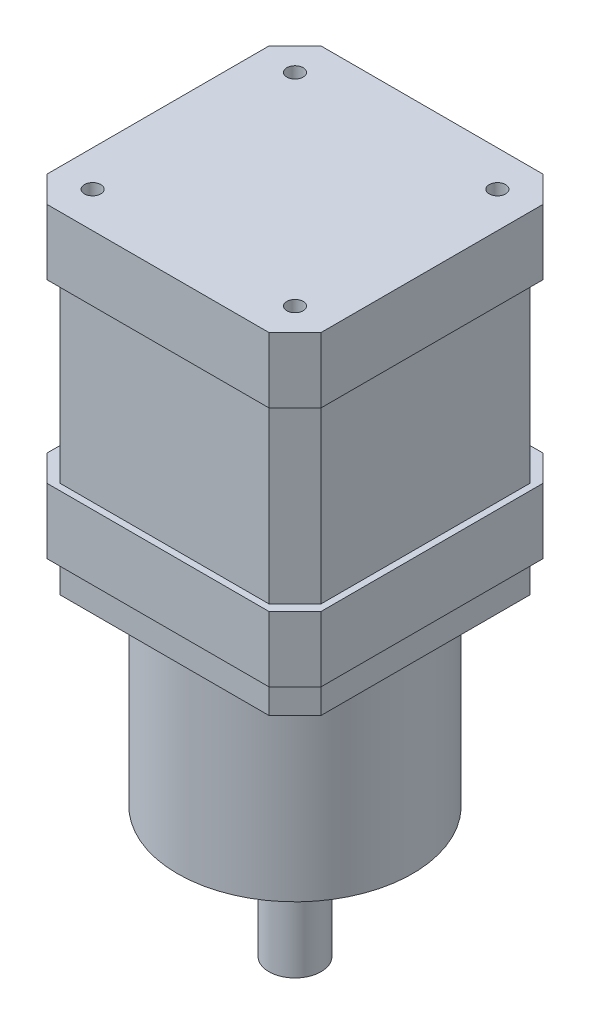
SolidWorks part; units mm, degrees
ref_plane "Front Plane" through (0, 0, 0) normal (0, 0, 1) x (1, 0, 0)
ref_plane "Top Plane" through (0, 0, 0) normal (0, 1, 0) x (1, 0, 0)
ref_plane "Right Plane" through (0, 0, 0) normal (1, 0, 0) x (0, 0, -1)
sketch "Sketch1" plane through (0, 0, 0) normal (0, 1, 0) x (1, 0, 0)
  line L1 (21, -21) -> (-21, -21)
  line L2 (21, -21) -> (21, 21)
  line L3 (21, 21) -> (-21, 21)
  line L4 (-21, -21) -> (-21, 21)
  line L5 (21, -21) -> (-21, 21) construction
  line L6 (21, 21) -> (-21, -21) construction
  point P0 (0, 0)
  dimension "D1" = 42
extrude "Boss-Extrude1" add sketch "Sketch1" along normal mid plane 47
sketch "Sketch2" plane through (0, 23.5, 0) normal (0, 1, 0) x (1, 0, 0)
  line L0 (-20, 20) -> (-20, -20)
  line L1 (-20, -20) -> (20, -20)
  line L2 (20, -20) -> (20, 20)
  line L3 (20, 20) -> (-20, 20)
  line L4 (-21, 21) -> (-21, -21)
  line L5 (-21, -21) -> (21, -21)
  line L6 (21, -21) -> (21, 21)
  line L7 (21, 21) -> (-21, 21)
  line L8 (-21, 21) -> (-21, -21)
  line L9 (-21, -21) -> (21, -21)
  line L10 (21, -21) -> (21, 21)
  line L11 (21, 21) -> (-21, 21)
  dimension "D1" = 0
  dimension "D2" = 1
extrude "Cut-Extrude1" cut sketch "Sketch2" against normal blind 27 from offset 10 offset against normal yes
chamfer "Chamfer1" distance 4 angle 45 1 edges at (-20, 0, 20)
sketch "Sketch4" plane through (0, 23.5, 0) normal (0, 1, 0) x (1, 0, 0)
  line L1 (-15.5, -15.5) -> (15.5, -15.5) construction
  line L2 (-15.5, -15.5) -> (-15.5, 15.5) construction
  line L3 (-15.5, 15.5) -> (15.5, 15.5) construction
  line L4 (15.5, -15.5) -> (15.5, 15.5) construction
  line L5 (-15.5, -15.5) -> (15.5, 15.5) construction
  line L6 (-15.5, 15.5) -> (15.5, -15.5) construction
  circle A0 centre (15.5, 15.5) radius 1.25
  circle A1 centre (15.5, -15.5) radius 1.25
  circle A2 centre (-15.5, -15.5) radius 1.25
  circle A3 centre (-15.5, 15.5) radius 1.25
  point P0 (0, 0)
  dimension "D2" = 2.5
  dimension "D1" = 31
extrude "Cut-Extrude2" cut sketch "Sketch4" against normal through all both and the other way through all
sketch "Sketch5" plane through (0, -23.5, 0) normal (0, -1, 0) x (1, 0, 0)
  line L0 (-20, 16) -> (-16, 20)
  line L1 (-16, -20) -> (16, -20)
  line L2 (-20, -16) -> (-20, 16)
  line L3 (-16, 20) -> (16, 20)
  line L4 (20, -16) -> (20, 16)
  line L5 (-20, -20) -> (20, 20) construction
  line L6 (-20, 20) -> (20, -20) construction
  line L7 (16, 20) -> (20, 16)
  line L8 (-20, -16) -> (-16, -20)
  line L9 (16, -20) -> (20, -16)
  point P0 (0, 0)
  dimension "D1" = 40
extrude "Boss-Extrude2" add sketch "Sketch5" along normal blind 4.8
sketch "Sketch6" plane through (0, -28.3, 0) normal (0, -1, 0) x (1, 0, 0)
  circle A0 centre (0, 0) radius 18
  dimension "D1" = 36
extrude "Boss-Extrude3" add sketch "Sketch6" along normal blind 30
sketch "Sketch7" plane through (0, -58.3, 0) normal (0, -1, 0) x (1, 0, 0)
  line L1 (-9.8995, -9.8995) -> (9.8995, -9.8995) construction
  line L2 (-9.8995, -9.8995) -> (-9.8995, 9.8995) construction
  line L3 (-9.8995, 9.8995) -> (9.8995, 9.8995) construction
  line L4 (9.8995, -9.8995) -> (9.8995, 9.8995) construction
  line L5 (-9.8995, -9.8995) -> (9.8995, 9.8995) construction
  line L6 (-9.8995, 9.8995) -> (9.8995, -9.8995) construction
  circle A0 centre (0, 0) radius 14 construction
  circle A1 centre (-9.8995, 9.8995) radius 1.25
  circle A2 centre (9.8995, 9.8995) radius 1.25
  circle A3 centre (9.8995, -9.8995) radius 1.25
  circle A4 centre (-9.8995, -9.8995) radius 1.25
  dimension "D1" = 28
  dimension "D2" = 2.5
extrude "Cut-Extrude3" cut sketch "Sketch7" against normal blind 4
sketch "Sketch8" plane through (0, -58.3, 0) normal (0, -1, 0) x (1, 0, 0)
  circle A0 centre (0, 0) radius 11
  dimension "D1" = 22
extrude "Boss-Extrude4" add sketch "Sketch8" along normal blind 2
sketch "Sketch9" plane through (0, -60.3, 0) normal (0, -1, 0) x (1, 0, 0)
  circle A0 centre (0, 0) radius 4
  dimension "D1" = 8
extrude "Boss-Extrude5" add sketch "Sketch9" along normal blind 18
sketch "Sketch10" plane through (0, -78.3, 0) normal (0, -1, 0) x (1, 0, 0)
  line L0 (-2.6458, 3) -> (2.6458, 3)
  circle A0 centre (0, 0) radius 4 construction
  arc A1 (2.6458, 3) -> (-2.6458, 3) centre (0, 0) ccw
extrude "Boss-Extrude6" add sketch "Sketch10" against normal blind 15
sketch "Sketch11" plane through (0, -58.3, 0) normal (0, -1, 0) x (1, 0, 0)
  circle A0 centre (0, 0) radius 11.5
  circle A1 centre (0, 0) radius 20
  circle A2 centre (-9.8995, 9.8995) radius 1.25
  circle A3 centre (9.8995, 9.8995) radius 1.25
  circle A4 centre (-9.8995, -9.8995) radius 1.25
  circle A5 centre (9.8995, -9.8995) radius 1.25
  circle A6 centre (0, 0) radius 18.5
  dimension "D1" = 23
  dimension "D2" = 40
  dimension "D3" = 37
equation "\"A\"= 42"
equation "\"D1@Sketch1\"=\"A\""
equation "\"L\"= 47"
equation "\"D1@Cut-Extrude1\"= \"L\" -20mm"
equation "\"D1@Sketch5\"= \"A\"  - 2"
equation "\"G\"= 34.8"
equation "\"D1@Boss-Extrude3\"=\"G\" - 4.8"
equation "\"D1@Boss-Extrude1\"= \"L\""
